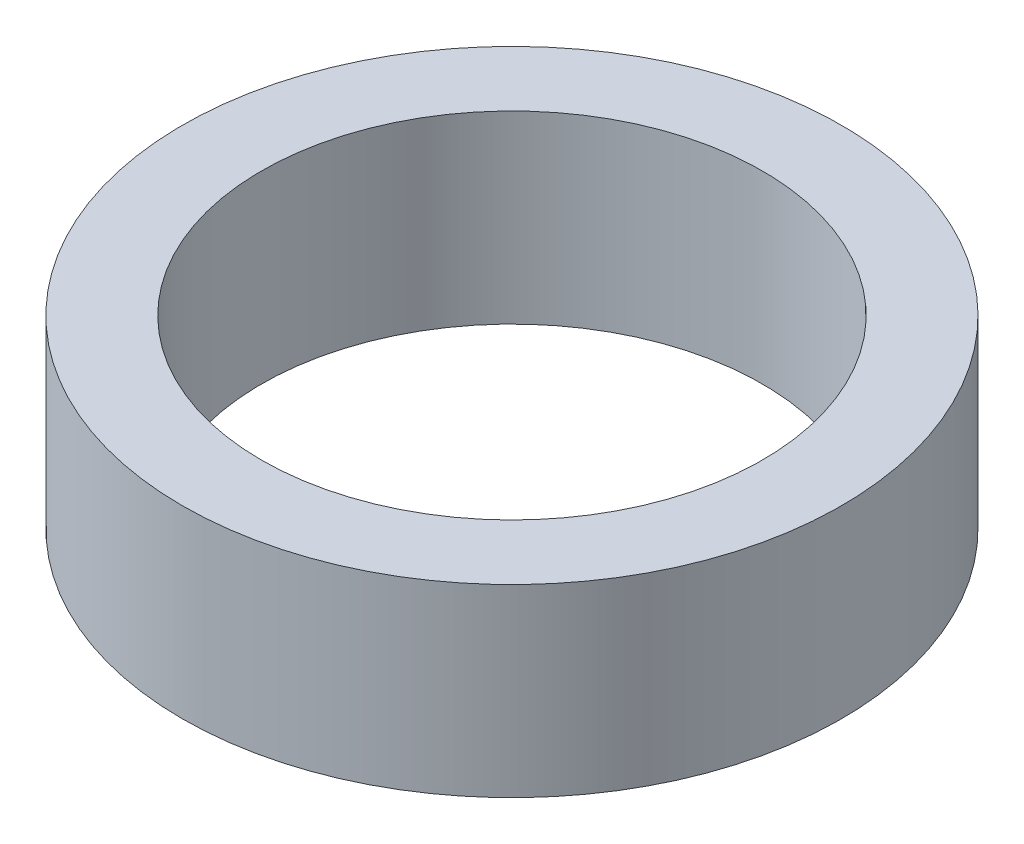
SolidWorks part; units mm, degrees
material "6061-T6 (SS)"
ref_plane "Front Plane" through (0, 0, 0) normal (0, 0, 1) x (1, 0, 0)
ref_plane "Top Plane" through (0, 0, 0) normal (0, 1, 0) x (1, 0, 0)
ref_plane "Right Plane" through (0, 0, 0) normal (1, 0, 0) x (0, 0, -1)
sketch "Sketch1" plane through (0, 0, 0) normal (0, 1, 0) x (1, 0, 0)
  circle A0 centre (0, 0) radius 6.25
  circle A1 centre (0, 0) radius 4.75
extrude "Boss-Extrude1" add sketch "Sketch1" along normal blind 3.5
